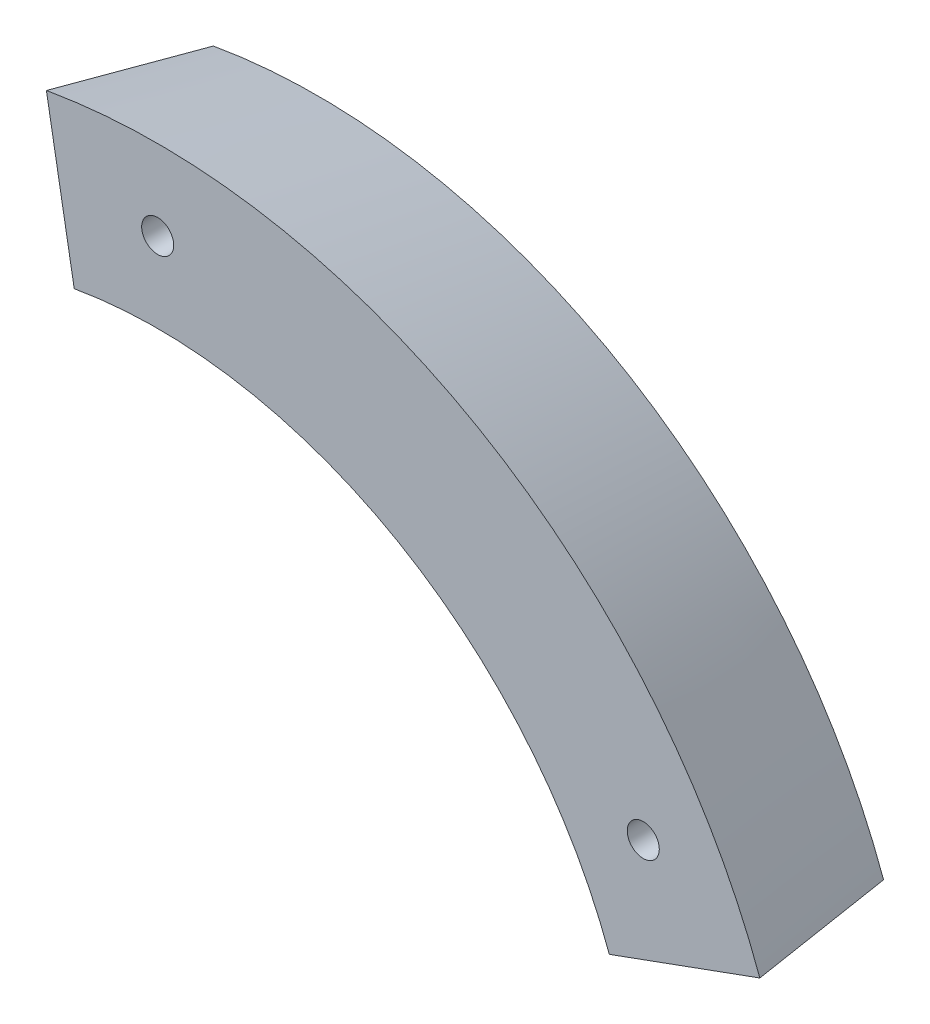
SolidWorks part; units mm, degrees
ref_plane "前视基准面" through (0, 0, 0) normal (0, 0, 1) x (1, 0, 0)
ref_plane "上视基准面" through (0, 0, 0) normal (0, 1, 0) x (1, 0, 0)
ref_plane "右视基准面" through (0, 0, 0) normal (1, 0, 0) x (0, 0, -1)
other "Configuration Table"
sketch "草图1" plane through (0, 0, 0) normal (0, 0, 1) x (1, 0, 0)
  line L0 (0, 1100) -> (0, 45) construction
  line L1 (-7.8142, 44.3163) -> (-10.4189, 59.0885)
  line L2 (42.2862, 15.3909) -> (56.3816, 20.5212)
  line L3 (45.4663, 26.25) -> (38.9711, 22.5) construction
  line L4 (0, 0) -> (0, -50000) construction
  arc A1 (-44.6979, 27.5382) -> (-46.1977, 24.9404) centre (0, 0) ccw
  circle A2 centre (0, 52.5) radius 1.5
  circle A3 centre (45.4663, 26.25) radius 1.5
  circle A4 centre (45.4663, -26.25) radius 1.5
  circle A5 centre (0, -52.5) radius 1.5
  circle A6 centre (-45.4663, -26.25) radius 1.5
  circle A7 centre (-45.4663, 26.25) radius 1.5
  arc A8 (56.3816, 20.5212) -> (-10.4189, 59.0885) centre (0, 0) ccw
  arc A9 (42.2862, 15.3909) -> (-7.8142, 44.3163) centre (0, 0) ccw
  arc A10 (44.6979, -27.5382) -> (46.1977, -24.9404) centre (0, 0) ccw
  arc A11 (-1.4998, -52.4786) -> (1.4998, -52.4786) centre (0, 0) ccw
  arc A12 (-46.1977, -24.9404) -> (-44.6979, -27.5382) centre (0, 0) ccw
  point P21 (0, 0)
  dimension "D1" = 3
  dimension "D2" = 105
  dimension "D3" = 6
  dimension "D4" = 10
  dimension "D7" = 45
  dimension "D5" = 10
  dimension "D6" = 60
extrude "凸台-拉伸1" add sketch "草图1" along normal blind 15 contours A9 L2 A8 L1 A3 A2
sketch "草图2" plane through (0, 0, 0) normal (0, 0, 1) x (1, 0, 0)
  circle A0 centre (0, 52.5) radius 3
  circle A1 centre (45.4663, 26.25) radius 3
  dimension "D1" = 6
  dimension "D2" = 6
extrude "切除-拉伸1" cut sketch "草图2" along normal blind 12
sketch "草图6" plane through (0, 0, 0) normal (-0.9848, -0.1736, 0) x (0, 0, 1)
  line L0 (0, 60) -> (0, 56.368)
  line L1 (0, 45) -> (0, 60) construction
  line L2 (0, 56.368) -> (15, 60)
  line L3 (15, 60) -> (0, 60)
  line L4 (0, 0) -> (-21.671, 0) construction
revolve "切除-旋转1" cut sketch "草图6" angle 360 about L4
